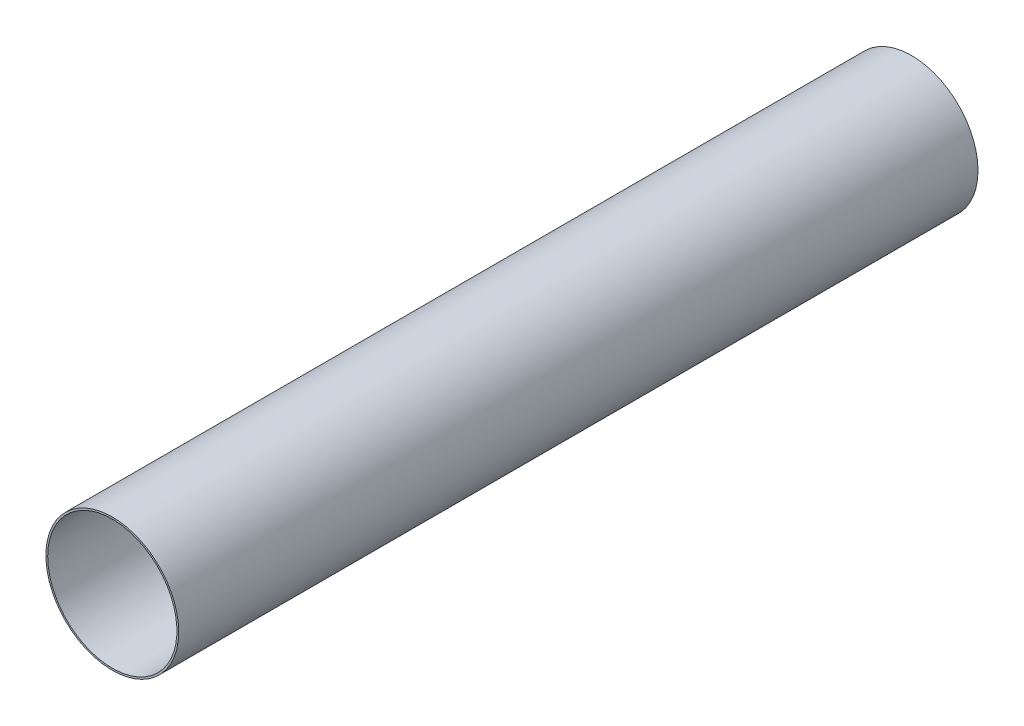
SolidWorks part; units mm, degrees
ref_plane "Front Plane" through (0, 0, 0) normal (0, 0, 1) x (1, 0, 0)
ref_plane "Top Plane" through (0, 0, 0) normal (0, 1, 0) x (1, 0, 0)
ref_plane "Right Plane" through (0, 0, 0) normal (1, 0, 0) x (0, 0, -1)
sketch "Sketch2" plane through (0, 0, 0) normal (0, 0, 1) x (1, 0, 0)
  circle A0 centre (0, 0) radius 46.6725
  dimension "D1" = 93.345
extrude "Boss-Extrude1" add sketch "Sketch2" along normal blind 561.6448
sketch "Sketch3" plane through (0, 0, 0) normal (0, 0, -1) x (-1, 0, 0)
  circle A0 centre (0, 0) radius 45.4025
  dimension "D1" = 90.805
extrude "Cut-Extrude1" cut sketch "Sketch3" against normal through all
